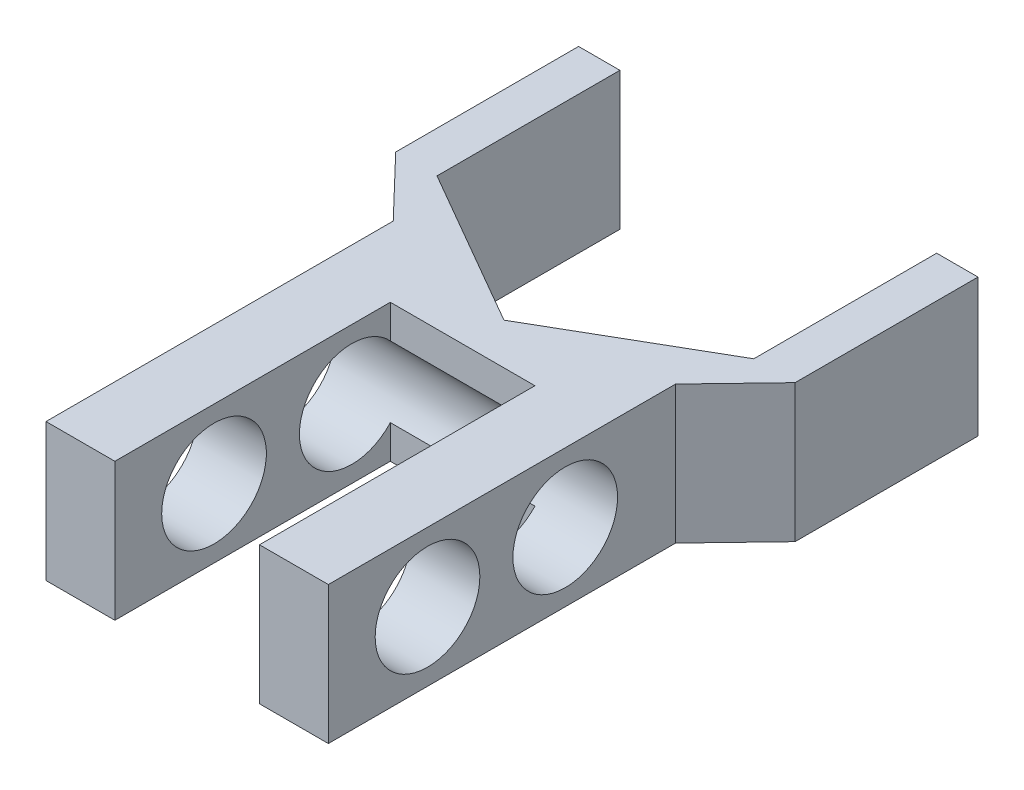
SolidWorks part; units mm, degrees
ref_plane "Front Plane" through (0, 0, 0) normal (0, 0, 1) x (1, 0, 0)
ref_plane "Top Plane" through (0, 0, 0) normal (0, 1, 0) x (1, 0, 0)
ref_plane "Right Plane" through (0, 0, 0) normal (1, 0, 0) x (0, 0, -1)
sketch "Sketch1" plane through (0, 0, 0) normal (0, 1, 0) x (1, 0, 0)
  line L0 (-14.5, -6.6395) -> (-5.25, -16.2791)
  line L1 (10, -5.7735) -> (10, 5.7735)
  line L2 (10, 5.7735) -> (0, 11.547)
  line L3 (0, 11.547) -> (-10, 5.7735)
  line L4 (-10, 5.7735) -> (-10, -5.7735)
  line L5 (-10, -5.7735) -> (0, -11.547)
  line L6 (0, -11.547) -> (10, -5.7735)
  line L7 (-11.5, 6.6395) -> (-14.5, 6.6395)
  line L9 (-11.5, -6.6395) -> (-14.5, -6.6395)
  line L10 (-14.5, 6.6395) -> (-14.5, -6.6395)
  line L11 (11.5, 6.6395) -> (14.5, 6.6395)
  line L13 (11.5, -6.6395) -> (14.5, -6.6395)
  line L14 (14.5, 6.6395) -> (14.5, -6.6395)
  line L15 (0, -13.2791) -> (11.5, -6.6395)
  line L16 (11.5, -6.6395) -> (11.5, 6.6395)
  line L17 (11.5, 6.6395) -> (0, 13.2791)
  line L18 (0, 13.2791) -> (-11.5, 6.6395)
  line L19 (-11.5, 6.6395) -> (-11.5, -6.6395)
  line L20 (-11.5, -6.6395) -> (0, -13.2791)
  line L21 (-12.6269, -8.5915) -> (-11.5, -6.6395)
  line L23 (5.25, -16.2791) -> (14.5, -6.6395)
  line L24 (-5.25, -16.2791) -> (5.25, -16.2791)
  line L25 (-10.25, -11.0685) -> (-10.25, -36.2791)
  line L26 (10.25, -11.0685) -> (10.25, -36.2791)
  line L27 (-10.25, -36.2791) -> (-5.25, -36.2791)
  line L28 (-5.25, -36.2791) -> (-5.25, -16.2791)
  line L29 (10.25, -36.2791) -> (5.25, -36.2791)
  line L30 (5.25, -36.2791) -> (5.25, -16.2791)
  line L31 (5.25, -16.2791) -> (-5.25, -16.2791)
  line L32 (12.6269, -8.5915) -> (11.5, -6.6395)
  circle A0 centre (0, 0) radius 10 construction
  circle A1 centre (0, 0) radius 11.5 construction
  dimension "D1" = 20
  dimension "D2" = 23
  dimension "D3" = 3
  dimension "D4" = 10.5
  dimension "D5" = 5
  dimension "D6" = 20
  dimension "D7" = 3
extrude "Boss-Extrude1" add sketch "Sketch1" along normal blind 10
sketch "Sketch3" plane through (-10.25, 0, 0) normal (-1, 0, 0) x (0, 0, 1)
  line L0 (19.0791, 5) -> (29.0791, 5) construction
  line L1 (19.0791, 10.8) -> (29.0791, 10.8)
  line L2 (19.0791, -0.8) -> (29.0791, -0.8)
  line L3 (13.2791, 10) -> (13.2791, 0) construction
  line L4 (36.2791, 10) -> (36.2791, 0) construction
  line L5 (24.0791, 10) -> (24.0791, 0)
  line L6 (11.0685, 10) -> (36.2791, 10) construction
  line L7 (11.0685, 0) -> (36.2791, 0) construction
  circle A0 centre (19.0791, 5) radius 3.8
  circle A1 centre (29.0791, 5) radius 3.8
  arc A2 (19.0791, 10.8) -> (19.0791, -0.8) centre (19.0791, 5) ccw
  arc A3 (29.0791, -0.8) -> (29.0791, 10.8) centre (29.0791, 5) ccw
  point P4 (24.0791, 5)
  point P13 (0, 0)
  dimension "D1" = 7.6
  dimension "D2" = 2
  dimension "D3" = 10
extrude "Cut-Extrude1" cut sketch "Sketch3" against normal through all
